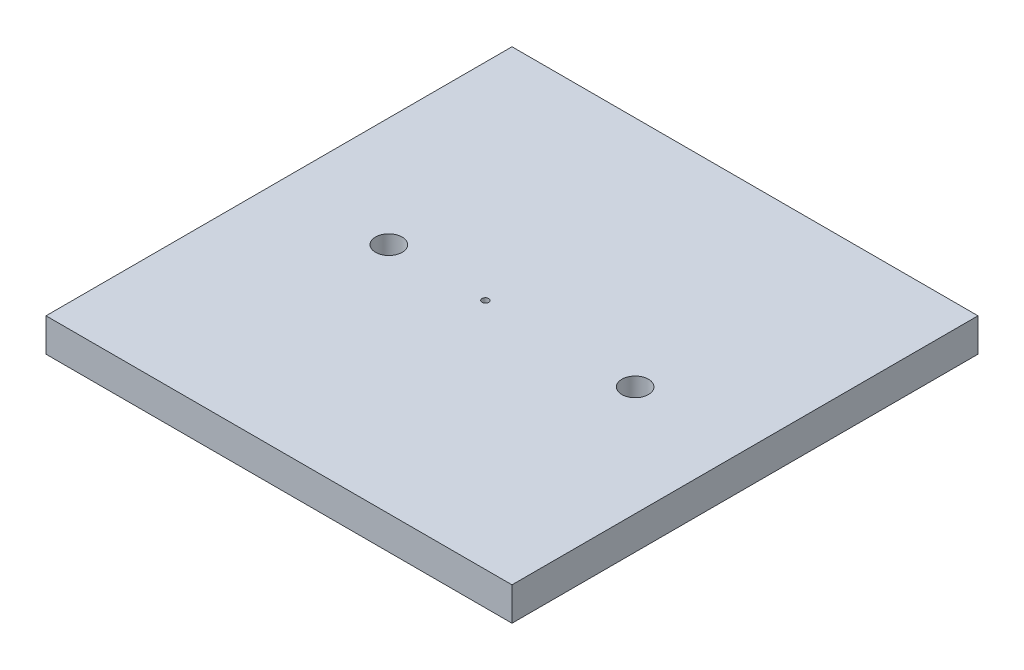
SolidWorks part; units mm, degrees
ref_plane "Front Plane" through (0, 0, 0) normal (0, 0, 1) x (1, 0, 0)
ref_plane "Top Plane" through (0, 0, 0) normal (0, 1, 0) x (1, 0, 0)
ref_plane "Right Plane" through (0, 0, 0) normal (1, 0, 0) x (0, 0, -1)
sketch "Sketch1" plane through (0, 0, 0) normal (0, 1, 0) x (1, 0, 0)
  line L1 (-35, 35) -> (35, 35)
  line L2 (-35, 35) -> (-35, -35)
  line L3 (-35, -35) -> (35, -35)
  line L4 (35, 35) -> (35, -35)
  line L5 (-35, 35) -> (35, -35) construction
  line L6 (-35, -35) -> (35, 35) construction
  point P0 (0, 0)
  dimension "D1" = 70
  dimension "D2" = 70
extrude "Boss-Extrude1" add sketch "Sketch1" along normal blind 5 contours L1 L4 L3 L2
sketch "Sketch2" plane through (0, 0, 0) normal (0, -1, 0) x (1, 0, 0)
  line L0 (-25.5, 0) -> (25.5, 0) construction
  line L1 (0, 25.5) -> (0, -25.5) construction
  circle A0 centre (0, 0) radius 25.5
  circle A1 centre (-18.5, 0) radius 2
  circle A2 centre (18.5, 0) radius 2
  dimension "D1" = 51
  dimension "D2" = 4
  dimension "D3" = 18.5
extrude "Cut-Extrude3" cut sketch "Sketch2" against normal blind 2
sketch "Sketch3" plane through (0, 0, 0) normal (0, -1, 0) x (1, 0, 0)
  circle A0 centre (18.5, 0) radius 2
  circle A1 centre (18.5, 0) radius 2 construction
  dimension "D1" = 4
extrude "Cut-Extrude4" cut sketch "Sketch3" against normal blind 10
sketch "Sketch4" plane through (0, 0, 0) normal (0, -1, 0) x (-1, 0, 0)
  circle A0 centre (18.5, 0) radius 2
  circle A1 centre (18.5, 0) radius 2 construction
  dimension "D1" = 4
extrude "Cut-Extrude5" cut sketch "Sketch4" against normal blind 10
sketch "Sketch5" plane through (0, 2, 0) normal (0, -1, 0) x (-1, 0, 0)
  circle A1 centre (-4, 0) radius 0.5
  circle A2 centre (4, 0) radius 0.5
  dimension "D2" = 1
  dimension "D3" = 1
extrude "Cut-Extrude7" cut sketch "Sketch5" against normal blind 10 contours A2
